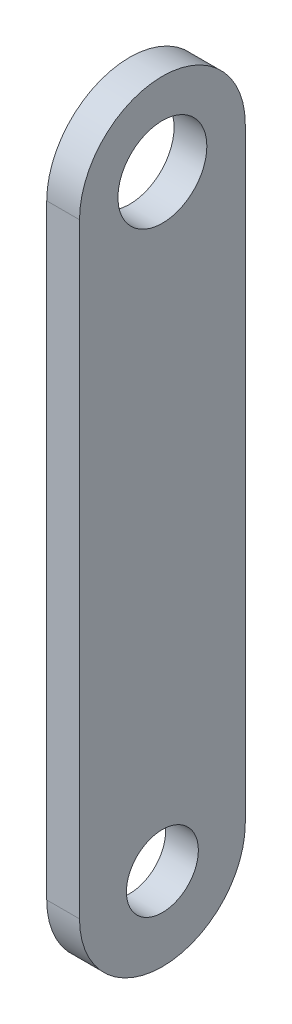
SolidWorks part; units mm, degrees
material "Delrin 2700 NC010，低粘度乙缩醛共聚物 (SS)"
ref_plane "前视基准面" through (0, 0, 0) normal (0, 0, 1) x (1, 0, 0)
ref_plane "上视基准面" through (0, 0, 0) normal (0, 1, 0) x (1, 0, 0)
ref_plane "右视基准面" through (0, 0, 0) normal (1, 0, 0) x (0, 0, -1)
sketch "草图1" plane through (0, 0, 0) normal (1, 0, 0) x (0, 0, -1)
  line L0 (0, 0) -> (0, 92.4) construction
  line L1 (-12.6475, 0) -> (-12.6475, 92.4)
  line L2 (12.6475, 0) -> (12.6475, 92.4)
  arc A0 (-12.6475, 0) -> (12.6475, 0) centre (0, 0) ccw
  arc A1 (12.6475, 92.4) -> (-12.6475, 92.4) centre (0, 92.4) ccw
  circle A2 centre (0, 92.4) radius 6.7835
  circle A3 centre (0, 0) radius 5.4912
  point P3 (0, 46.2)
  dimension "D1" = 92.4
extrude "凸台-拉伸1" add sketch "草图1" along normal blind 5
